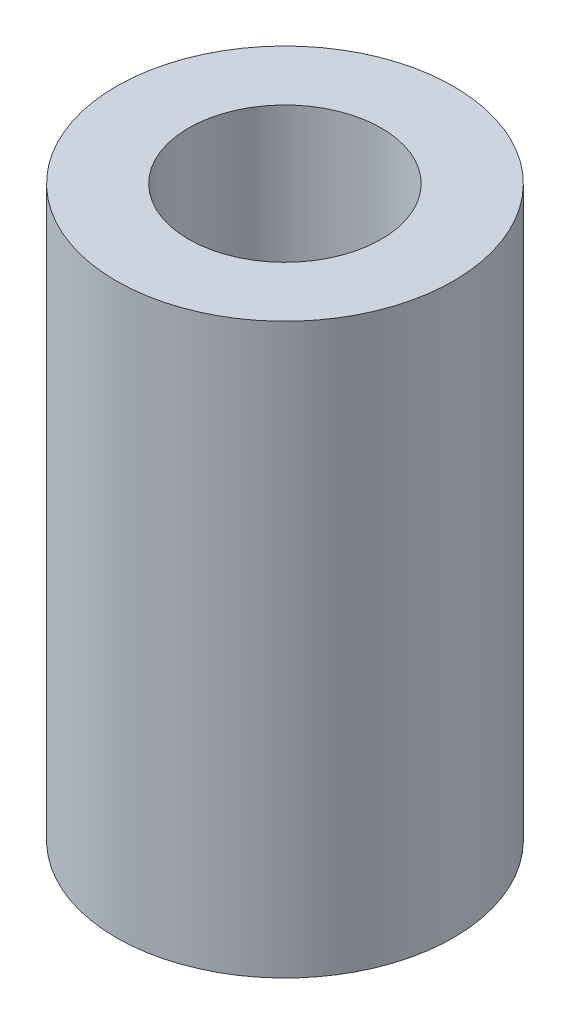
SolidWorks part; units mm, degrees
ref_plane "Front" through (0, 0, 0) normal (0, 0, 1) x (1, 0, 0)
ref_plane "Top" through (0, 0, 0) normal (0, 1, 0) x (1, 0, 0)
ref_plane "Right" through (0, 0, 0) normal (1, 0, 0) x (0, 0, -1)
sketch "Sketch2" plane through (0, 0, 0) normal (0, 1, 0) x (1, 0, 0)
  circle A0 centre (0, 0) radius 5.335
  circle A1 centre (0, 0) radius 3.05
  dimension "D1" = 10.67
  dimension "D2" = 6.1
extrude "Boss-Extrude1" add sketch "Sketch2" along normal blind 18
